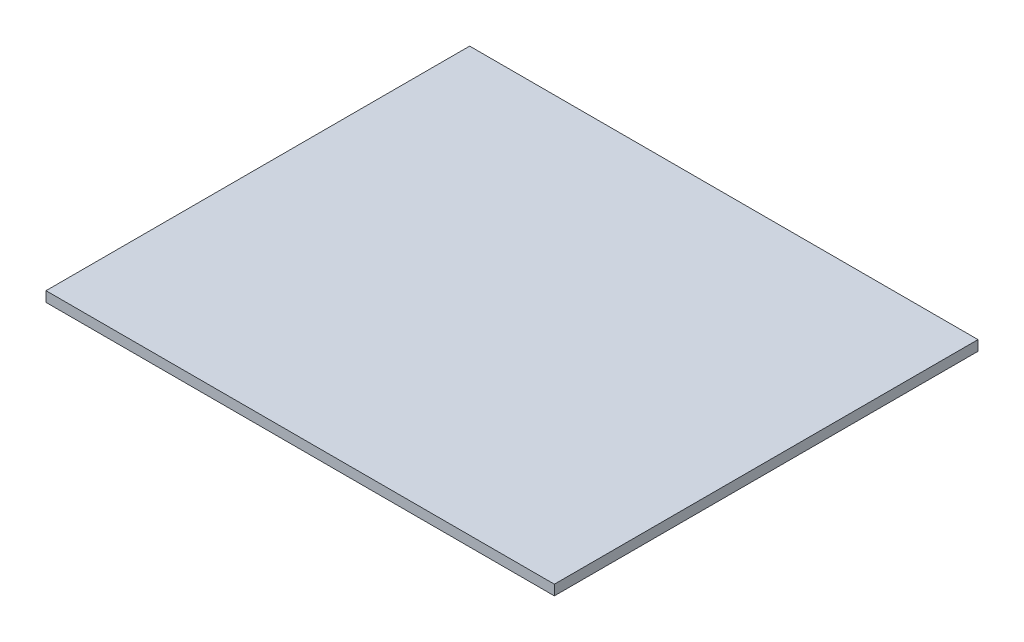
SolidWorks part; units mm, degrees
ref_plane "前视基准面" through (0, 0, 0) normal (0, 0, 1) x (1, 0, 0)
ref_plane "上视基准面" through (0, 0, 0) normal (0, 1, 0) x (1, 0, 0)
ref_plane "右视基准面" through (0, 0, 0) normal (1, 0, 0) x (0, 0, -1)
sketch "草图1" plane through (0, 0, 0) normal (0, 1, 0) x (1, 0, 0)
  line L1 (-160.0547, 275.7866) -> (739.9453, 275.7866)
  line L2 (-160.0547, 275.7866) -> (-160.0547, -474.2134)
  line L3 (-160.0547, -474.2134) -> (739.9453, -474.2134)
  line L4 (739.9453, 275.7866) -> (739.9453, -474.2134)
  dimension "D1" = 900
  dimension "D2" = 750
extrude "凸台-拉伸1" add sketch "草图1" along normal blind 18
